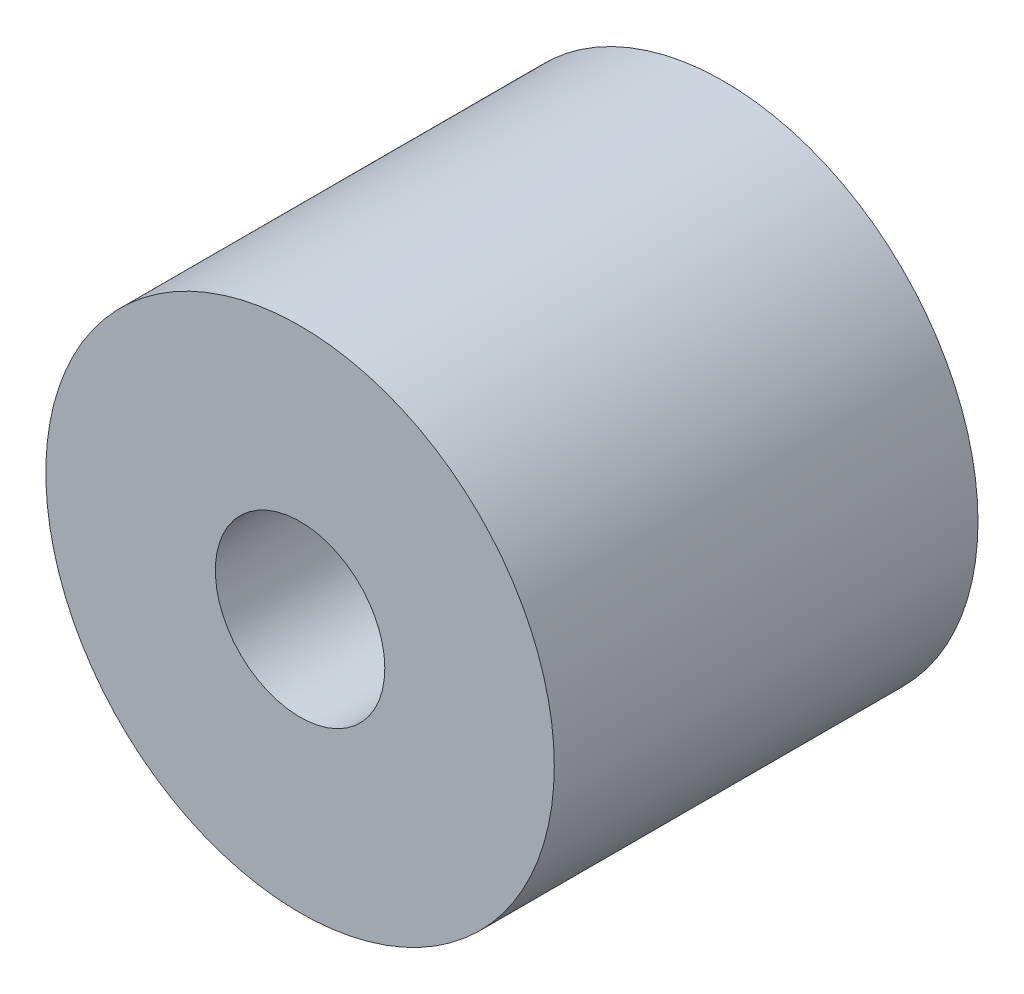
SolidWorks part; units mm, degrees
material "ABS"
ref_plane "前视基准面" through (0, 0, 0) normal (0, 0, 1) x (1, 0, 0)
ref_plane "上视基准面" through (0, 0, 0) normal (0, 1, 0) x (1, 0, 0)
ref_plane "右视基准面" through (0, 0, 0) normal (1, 0, 0) x (0, 0, -1)
sketch "草图1" plane through (0, 0, 0) normal (0, 0, 1) x (1, 0, 0)
  circle A0 centre (0, 0) radius 3
  dimension "D1" = 6
extrude "凸台-拉伸1" add sketch "草图1" along normal blind 5
sketch "草图2" plane through (0, 0, 5) normal (0, 0, 1) x (1, 0, 0)
  circle A0 centre (0, 0) radius 1
  dimension "D1" = 2
extrude "切除-拉伸1" cut sketch "草图2" against normal through all
